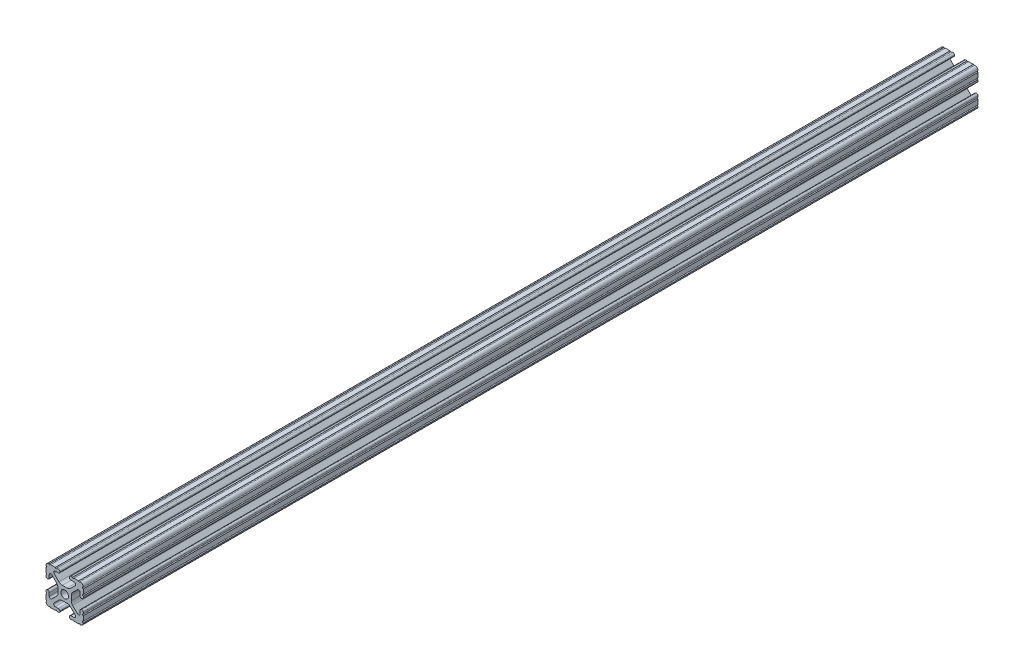
SolidWorks part; units mm, degrees
ref_plane "Front Plane" through (0, 0, 0) normal (0, 0, 1) x (1, 0, 0)
ref_plane "Top Plane" through (0, 0, 0) normal (0, 1, 0) x (1, 0, 0)
ref_plane "Right Plane" through (0, 0, 0) normal (1, 0, 0) x (0, 0, -1)
ref_plane "Plane1" through (0, 0, -609.6) normal (0, 0, -1) x (-1, 0, 0)
sketch "Sketch1" plane through (0, 0, -609.6) normal (0, 0, -1) x (-1, 0, 0)
  line L0 (3.9523, -5.4237) -> (7.1797, -8.6452)
  line L1 (6.4164, -10.4902) -> (4.2875, -10.4902)
  line L2 (3.2385, -11.5392) -> (3.2385, -11.651)
  line L3 (4.2875, -12.7) -> (5.3171, -12.7)
  line L4 (6.3331, -12.7) -> (9.5504, -12.7)
  line L5 (12.7, -9.5504) -> (12.7, -6.3331)
  line L6 (12.7, -5.3171) -> (12.7, -4.2875)
  line L7 (11.651, -3.2385) -> (11.5392, -3.2385)
  line L8 (10.4902, -4.2875) -> (10.4902, -6.4021)
  line L9 (8.7371, -7.1294) -> (5.441, -3.8408)
  line L10 (4.5085, -1.5932) -> (4.5085, 1.5932)
  line L11 (5.441, 3.8408) -> (8.7371, 7.1294)
  line L12 (10.4902, 6.4021) -> (10.4902, 4.2875)
  line L13 (11.5392, 3.2385) -> (11.651, 3.2385)
  line L14 (12.7, 4.2875) -> (12.7, 5.3171)
  line L15 (12.7, 6.3331) -> (12.7, 9.5504)
  line L16 (9.5504, 12.7) -> (6.3331, 12.7)
  line L17 (5.3171, 12.7) -> (4.2875, 12.7)
  line L18 (3.2385, 11.651) -> (3.2385, 11.5392)
  line L19 (4.2875, 10.4902) -> (6.4768, 10.4902)
  line L20 (7.207, 8.7244) -> (3.8983, 5.4232)
  line L21 (1.6558, 4.4958) -> (-1.6558, 4.4958)
  line L22 (-3.8983, 5.4232) -> (-7.207, 8.7244)
  line L23 (-6.4768, 10.4902) -> (-4.2875, 10.4902)
  line L24 (-3.2385, 11.5392) -> (-3.2385, 11.651)
  line L25 (-4.2875, 12.7) -> (-5.3171, 12.7)
  line L26 (-6.3331, 12.7) -> (-9.5504, 12.7)
  line L27 (-12.7, 9.5504) -> (-12.7, 6.3331)
  line L28 (-12.7, 5.3171) -> (-12.7, 4.2875)
  line L29 (-11.651, 3.2385) -> (-11.5392, 3.2385)
  line L30 (-10.4902, 4.2875) -> (-10.4902, 6.4021)
  line L31 (-8.7371, 7.1294) -> (-5.441, 3.8408)
  line L32 (-4.5085, 1.5932) -> (-4.5085, -1.5932)
  line L33 (-5.441, -3.8408) -> (-8.7371, -7.1294)
  line L34 (-10.4902, -6.4021) -> (-10.4902, -4.2875)
  line L35 (-11.5392, -3.2385) -> (-11.651, -3.2385)
  line L36 (-12.7, -4.2875) -> (-12.7, -5.3171)
  line L37 (-12.7, -6.3331) -> (-12.7, -9.5504)
  line L38 (-9.5504, -12.7) -> (-6.3331, -12.7)
  line L39 (-5.3171, -12.7) -> (-4.2875, -12.7)
  line L40 (-3.2385, -11.651) -> (-3.2385, -11.5392)
  line L41 (-4.2875, -10.4902) -> (-6.4164, -10.4902)
  line L42 (-7.1797, -8.6452) -> (-3.9523, -5.4237)
  line L43 (-1.7093, -4.4958) -> (1.7093, -4.4958)
  circle A0 centre (0, 0) radius 2.6035
  arc A1 (7.1797, -8.6452) -> (6.4164, -10.4902) centre (6.4164, -9.4098) cw
  arc A2 (4.2875, -10.4902) -> (3.2385, -11.5392) centre (4.2875, -11.5392) ccw
  arc A3 (3.2385, -11.651) -> (4.2875, -12.7) centre (4.2875, -11.651) ccw
  arc A4 (5.3171, -12.7) -> (6.3331, -12.7) centre (5.8251, -12.7) cw
  arc A5 (9.5504, -12.7) -> (10.5664, -12.6998) centre (10.0584, -12.7) cw
  arc A6 (10.5664, -12.6998) -> (12.6998, -10.5664) centre (10.5918, -10.5918) ccw
  arc A7 (12.6998, -10.5664) -> (12.7, -9.5504) centre (12.7, -10.0584) cw
  arc A8 (12.7, -6.3331) -> (12.7, -5.3171) centre (12.7, -5.8251) cw
  arc A9 (12.7, -4.2875) -> (11.651, -3.2385) centre (11.651, -4.2875) ccw
  arc A10 (11.5392, -3.2385) -> (10.4902, -4.2875) centre (11.5392, -4.2875) ccw
  arc A11 (10.4902, -6.4021) -> (8.7371, -7.1294) centre (9.4628, -6.4021) cw
  arc A12 (5.441, -3.8408) -> (4.5085, -1.5932) centre (7.6835, -1.5932) cw
  arc A13 (4.5085, 1.5932) -> (5.441, 3.8408) centre (7.6835, 1.5932) cw
  arc A14 (8.7371, 7.1294) -> (10.4902, 6.4021) centre (9.4628, 6.4021) cw
  arc A15 (10.4902, 4.2875) -> (11.5392, 3.2385) centre (11.5392, 4.2875) ccw
  arc A16 (11.651, 3.2385) -> (12.7, 4.2875) centre (11.651, 4.2875) ccw
  arc A17 (12.7, 5.3171) -> (12.7, 6.3331) centre (12.7, 5.8251) cw
  arc A18 (12.7, 9.5504) -> (12.6998, 10.5664) centre (12.7, 10.0584) cw
  arc A19 (12.6998, 10.5664) -> (10.5664, 12.6998) centre (10.5918, 10.5918) ccw
  arc A20 (10.5664, 12.6998) -> (9.5504, 12.7) centre (10.0584, 12.7) cw
  arc A21 (6.3331, 12.7) -> (5.3171, 12.7) centre (5.8251, 12.7) cw
  arc A22 (4.2875, 12.7) -> (3.2385, 11.651) centre (4.2875, 11.651) ccw
  arc A23 (3.2385, 11.5392) -> (4.2875, 10.4902) centre (4.2875, 11.5392) ccw
  arc A24 (6.4768, 10.4902) -> (7.207, 8.7244) centre (6.4768, 9.4563) cw
  arc A25 (3.8983, 5.4232) -> (1.6558, 4.4958) centre (1.6558, 7.6708) cw
  arc A26 (-1.6558, 4.4958) -> (-3.8983, 5.4232) centre (-1.6558, 7.6708) cw
  arc A27 (-7.207, 8.7244) -> (-6.4768, 10.4902) centre (-6.4768, 9.4563) cw
  arc A28 (-4.2875, 10.4902) -> (-3.2385, 11.5392) centre (-4.2875, 11.5392) ccw
  arc A29 (-3.2385, 11.651) -> (-4.2875, 12.7) centre (-4.2875, 11.651) ccw
  arc A30 (-5.3171, 12.7) -> (-6.3331, 12.7) centre (-5.8251, 12.7) cw
  arc A31 (-9.5504, 12.7) -> (-10.5664, 12.6998) centre (-10.0584, 12.7) cw
  arc A32 (-10.5664, 12.6998) -> (-12.6998, 10.5664) centre (-10.5918, 10.5918) ccw
  arc A33 (-12.6998, 10.5664) -> (-12.7, 9.5504) centre (-12.7, 10.0584) cw
  arc A34 (-12.7, 6.3331) -> (-12.7, 5.3171) centre (-12.7, 5.8251) cw
  arc A35 (-12.7, 4.2875) -> (-11.651, 3.2385) centre (-11.651, 4.2875) ccw
  arc A36 (-11.5392, 3.2385) -> (-10.4902, 4.2875) centre (-11.5392, 4.2875) ccw
  arc A37 (-10.4902, 6.4021) -> (-8.7371, 7.1294) centre (-9.4628, 6.4021) cw
  arc A38 (-5.441, 3.8408) -> (-4.5085, 1.5932) centre (-7.6835, 1.5932) cw
  arc A39 (-4.5085, -1.5932) -> (-5.441, -3.8408) centre (-7.6835, -1.5932) cw
  arc A40 (-8.7371, -7.1294) -> (-10.4902, -6.4021) centre (-9.4628, -6.4021) cw
  arc A41 (-10.4902, -4.2875) -> (-11.5392, -3.2385) centre (-11.5392, -4.2875) ccw
  arc A42 (-11.651, -3.2385) -> (-12.7, -4.2875) centre (-11.651, -4.2875) ccw
  arc A43 (-12.7, -5.3171) -> (-12.7, -6.3331) centre (-12.7, -5.8251) cw
  arc A44 (-12.7, -9.5504) -> (-12.6998, -10.5664) centre (-12.7, -10.0584) cw
  arc A45 (-12.6998, -10.5664) -> (-10.5664, -12.6998) centre (-10.5918, -10.5918) ccw
  arc A46 (-10.5664, -12.6998) -> (-9.5504, -12.7) centre (-10.0584, -12.7) cw
  arc A47 (-6.3331, -12.7) -> (-5.3171, -12.7) centre (-5.8251, -12.7) cw
  arc A48 (-4.2875, -12.7) -> (-3.2385, -11.651) centre (-4.2875, -11.651) ccw
  arc A49 (-3.2385, -11.5392) -> (-4.2875, -10.4902) centre (-4.2875, -11.5392) ccw
  arc A50 (-6.4164, -10.4902) -> (-7.1797, -8.6452) centre (-6.4164, -9.4098) cw
  arc A51 (-3.9523, -5.4237) -> (-1.7093, -4.4958) centre (-1.7093, -7.6708) cw
  arc A52 (1.7093, -4.4958) -> (3.9523, -5.4237) centre (1.7093, -7.6708) cw
extrude "Boss-Extrude1" add sketch "Sketch1" against normal blind 609.6
